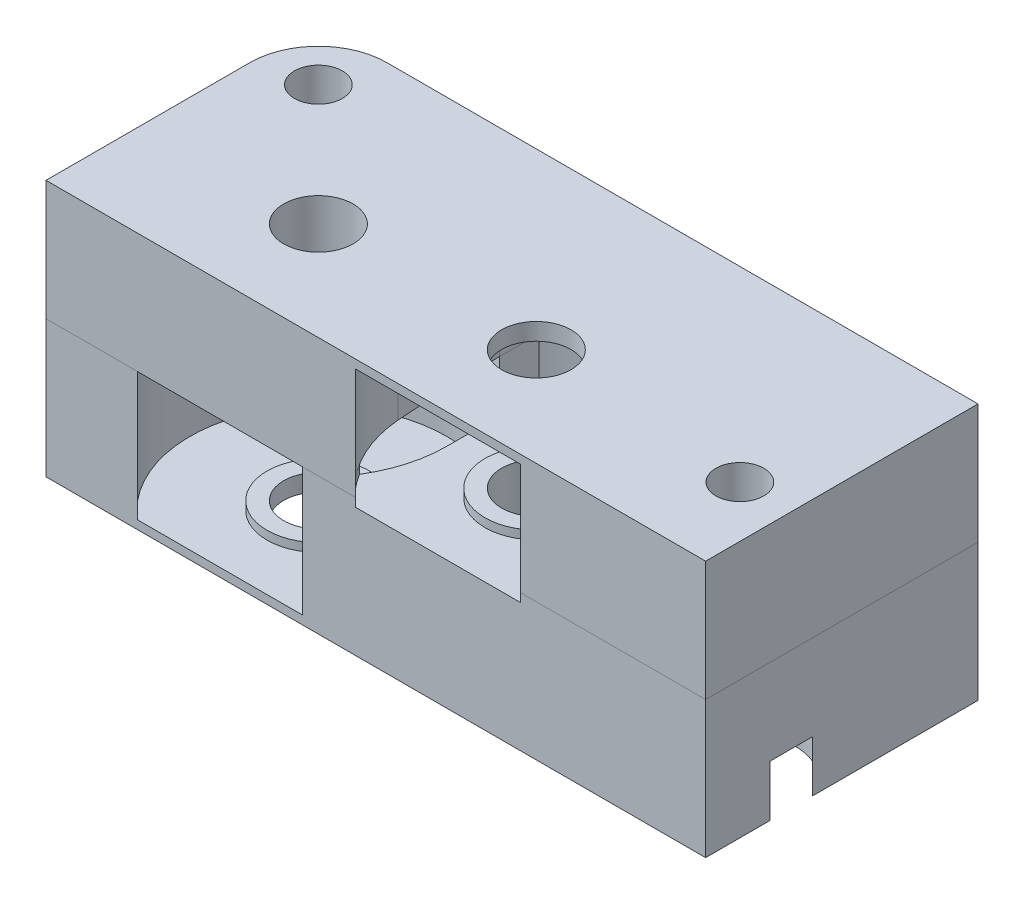
SolidWorks part; units mm, degrees
ref_plane "Front Plane" through (0, 0, 0) normal (0, 0, 1) x (1, 0, 0)
ref_plane "Top Plane" through (0, 0, 0) normal (0, 1, 0) x (1, 0, 0)
ref_plane "Right Plane" through (0, 0, 0) normal (1, 0, 0) x (0, 0, -1)
sketch "Sketch1" plane through (0, 0, 0) normal (0, 1, 0) x (1, 0, 0)
  line L0 (0, 5.75) -> (38.53, 5.75) construction
  line L1 (0, 0) -> (38.53, 0)
  line L2 (0, 0) -> (0, 15.91)
  line L3 (0, 15.91) -> (38.53, 15.91)
  line L4 (38.53, 0) -> (38.53, 15.91)
  circle A0 centre (10.16, 5.75) radius 2.025
  circle A1 centre (22.89, 5.75) radius 2.025
  circle A2 centre (22.89, 5.75) radius 6 construction
  circle A3 centre (10.16, 5.75) radius 6 construction
  dimension "D3" = 4.05
  dimension "D7" = 12
  dimension "D8" = 12
  dimension "D1" = 5.75
  dimension "D2" = 12.73
  dimension "D4" = 38.53
  dimension "D5" = 10.16
  dimension "D6" = 10.16
extrude "Boss-Extrude1" add sketch "Sketch1" along normal blind 8 contours L2 L3 L4 L1
sketch "Sketch2" plane through (0, 8, 0) normal (0, 1, 0) x (1, 0, 0)
  line L0 (17.66, 5.75) -> (17.66, 15.91)
  line L1 (38.53, 15.91) -> (0, 15.91) construction
  line L2 (17.66, 15.91) -> (15.16, 15.91)
  line L3 (0, 0) -> (0, -1.75)
  line L4 (0, 15.91) -> (0, 0) construction
  line L5 (0, -1.75) -> (10.16, -1.75)
  line L6 (15.16, 11.3402) -> (15.16, 15.91)
  line L7 (5.3447, 0) -> (0, 0)
  arc A0 (10.16, -1.75) -> (17.66, 5.75) centre (10.16, 5.75) ccw
  arc A1 (15.16, 11.3402) -> (5.3447, 0) centre (10.16, 5.75) ccw
  point P7 (0, 0)
  dimension "D1" = 7.5
  dimension "D3" = 2.5
extrude "Cut-Extrude1" cut sketch "Sketch2" against normal offset from surface (7 mm away) 1 up to face at (10.16, 0, -3.725)
sketch "Sketch3" plane through (0, 1, 0) normal (0, 1, 0) x (1, 0, 0)
  line L4 (17.66, 5.75) -> (17.66, 15.91)
  line L5 (17.66, 15.91) -> (15.16, 15.91)
  line L7 (5.3447, 0) -> (14.9753, 0)
  line L8 (17.66, 5.75) -> (17.66, 15.91)
  line L9 (17.66, 15.91) -> (15.16, 15.91)
  line L16 (15.16, 15.91) -> (15.16, 11.3402)
  line L17 (15.16, 15.91) -> (15.16, 11.3402)
  line L18 (5.3447, 0) -> (14.9753, 0)
  circle A0 centre (10.16, 5.75) radius 3
  arc A1 (14.9753, 0) -> (17.66, 5.75) centre (10.16, 5.75) ccw
  arc A2 (14.9753, 0) -> (17.66, 5.75) centre (10.16, 5.75) ccw
  arc A5 (15.16, 11.3402) -> (5.3447, 0) centre (10.16, 5.75) ccw
  arc A6 (15.16, 11.3402) -> (5.3447, 0) centre (10.16, 5.75) ccw
  dimension "D2" = 6
  dimension "D1" = 0
extrude "Cut-Extrude2" cut sketch "Sketch3" against normal blind 0.5
sketch "Sketch5" plane through (0, 8, 0) normal (0, 1, 0) x (1, 0, 0)
  line L2 (17.66, 5.75) -> (17.66, 15.91) construction
  line L6 (17.66, 11.1256) -> (17.66, 5.75)
  circle A0 centre (22.89, 5.75) radius 3
  arc A1 (14.9753, 0) -> (17.66, 5.75) centre (10.16, 5.75) ccw construction
  circle A2 centre (22.89, 5.75) radius 2.025 construction
  arc A4 (16.525, 1.783) -> (17.66, 5.75) centre (10.16, 5.75) ccw
  arc A5 (16.525, 1.783) -> (17.66, 11.1256) centre (22.89, 5.75) ccw
  point P5 (17.66, 14.6335)
  point P9 (16.6678, 5.502)
  point P13 (17.66, 14.5938)
  point P16 (17.66, 9.23)
  dimension "D2" = 6
extrude "Cut-Extrude4" cut sketch "Sketch5" against normal blind 0.5
sketch "Sketch8" plane through (0, 8, 0) normal (0, 1, 0) x (1, 0, 0)
  line L1 (0, 0) -> (18.0747, 0)
  line L4 (27.7053, 0) -> (38.53, 0)
  line L5 (38.53, 0) -> (38.53, 15.91)
  line L6 (38.53, 15.91) -> (17.66, 15.91)
  line L7 (17.66, 15.91) -> (17.66, 11.1256)
  line L8 (27.7053, 0) -> (38.53, 0)
  line L9 (38.53, 0) -> (38.53, 15.91)
  line L10 (38.53, 15.91) -> (17.66, 15.91)
  line L14 (0, 15.91) -> (0, 0)
  line L15 (0, 0) -> (5.3447, 0)
  line L16 (15.16, 11.3402) -> (15.16, 15.91)
  line L17 (15.16, 15.91) -> (0, 15.91)
  line L18 (0, 15.91) -> (0, 0)
  line L21 (15.16, 15.91) -> (0, 15.91)
  line L27 (17.66, 15.91) -> (17.66, 11.1256)
  line L29 (15.16, 11.3402) -> (15.16, 15.91)
  arc A0 (18.0747, 0) -> (15.4153, 5.1339) centre (22.89, 5.75) cw
  arc A1 (27.7053, 0) -> (17.66, 11.1256) centre (22.89, 5.75) ccw
  arc A3 (15.16, 11.3402) -> (5.3447, 0) centre (10.16, 5.75) ccw
  arc A10 (15.16, 11.3402) -> (15.4153, 5.1339) centre (90.7098, 11.3402) ccw
  circle A13 centre (10.16, 5.75) radius 2.025 construction
  circle A14 centre (10.16, 5.75) radius 2.025
  arc A17 (27.7053, 0) -> (17.66, 11.1256) centre (22.89, 5.75) ccw
  point P0 (18.0747, 0)
  dimension "D1" = 0
  dimension "D3" = 0
extrude "Boss-Extrude3" add sketch "Sketch8" along normal blind 6 separate body
sketch "Sketch12" plane through (0, 8, 0) normal (0, -1, 0) x (1, 0, 0)
  line L1 (13.9924, -0.5) -> (6.3276, -0.5)
  line L7 (0, 0) -> (0, -15.91)
  line L8 (0, -15.91) -> (15.16, -15.91)
  line L9 (15.16, -15.91) -> (15.16, -11.3402)
  line L10 (18.0747, 0) -> (0, 0)
  line L14 (14.1522, 0) -> (6.1678, 0) construction
  circle A3 centre (10.16, -5.75) radius 2.025 construction
  circle A7 centre (10.16, -5.75) radius 2.025
  arc A9 (16.2402, -2.2815) -> (14.1522, 0) centre (10.16, -5.75) ccw construction
  arc A11 (6.1678, 0) -> (15.1632, -10.6457) centre (10.16, -5.75) ccw construction
  arc A12 (15.4153, -5.1339) -> (15.16, -11.3402) centre (90.7098, -11.3402) ccw
  arc A15 (18.0747, 0) -> (15.4153, -5.1339) centre (22.89, -5.75) ccw
  arc A16 (15.4153, -5.1339) -> (15.1632, -10.6457) centre (90.7098, -11.3402) ccw construction
  arc A17 (16.2402, -2.2815) -> (15.4153, -5.1339) centre (22.89, -5.75) ccw construction
  arc A18 (15.6707, -2.303) -> (14.917, -5.0928) centre (22.89, -5.75) ccw
  arc A19 (14.917, -5.0928) -> (14.6654, -10.4352) centre (90.7098, -11.3402) ccw
  arc A20 (6.3276, -0.5) -> (14.6654, -10.4352) centre (10.16, -5.75) ccw
  arc A21 (15.6707, -2.303) -> (13.9924, -0.5) centre (10.16, -5.75) ccw
  dimension "D1" = 0
  dimension "D2" = 14
  dimension "D3" = 0.5
extrude "Boss-Extrude5" add sketch "Sketch12" along normal blind 1
sketch "Sketch13" plane through (0, 7, 0) normal (0, -1, 0) x (1, 0, 0)
  line L1 (13.9924, -0.5) -> (6.3276, -0.5)
  line L4 (13.9924, -0.5) -> (6.3276, -0.5)
  circle A4 centre (10.16, -5.75) radius 3.025
  circle A5 centre (10.16, -5.75) radius 2.025 construction
  arc A8 (15.6707, -2.303) -> (13.9924, -0.5) centre (10.16, -5.75) ccw
  arc A9 (6.3276, -0.5) -> (14.6654, -10.4352) centre (10.16, -5.75) ccw
  arc A20 (14.917, -5.0928) -> (14.6654, -10.4352) centre (90.7098, -11.3402) ccw
  arc A21 (15.6707, -2.303) -> (14.917, -5.0928) centre (22.89, -5.75) ccw
  arc A22 (15.6707, -2.303) -> (13.9924, -0.5) centre (10.16, -5.75) ccw
  arc A23 (6.3276, -0.5) -> (14.6654, -10.4352) centre (10.16, -5.75) ccw
  arc A24 (14.917, -5.0928) -> (14.6654, -10.4352) centre (90.7098, -11.3402) ccw
  arc A25 (15.6707, -2.303) -> (14.917, -5.0928) centre (22.89, -5.75) ccw
  dimension "D1" = 0
  dimension "D2" = 1
extrude "Cut-Extrude6" cut sketch "Sketch13" against normal blind 0.5
sketch "Sketch14" plane through (0, 14, 0) normal (0, 1, 0) x (1, 0, 0)
  line L1 (0, 15.91) -> (38.53, 15.91)
  line L2 (0, 15.91) -> (0, 0)
  line L3 (0, 0) -> (38.53, 0)
  line L4 (38.53, 15.91) -> (38.53, 0)
  circle A0 centre (22.89, 5.75) radius 2.025 construction
  circle A1 centre (10.16, 5.75) radius 2.025 construction
  circle A2 centre (22.89, 5.75) radius 2.025
  circle A3 centre (10.16, 5.75) radius 2.025
  point P5 (0, 0)
  point P14 (0, 0)
extrude "Boss-Extrude6" add sketch "Sketch14" along normal blind 1
sketch "Sketch15" plane through (0, 14, 0) normal (0, -1, 0) x (1, 0, 0)
  line L4 (15.16, -11.3402) -> (15.16, -15.91)
  line L10 (15.16, -15.91) -> (17.66, -15.91)
  line L15 (15.16, -11.3402) -> (15.16, -15.91)
  line L18 (15.16, -15.91) -> (17.66, -15.91)
  line L26 (17.66, -15.91) -> (17.66, -11.1256)
  line L28 (17.66, -15.91) -> (17.66, -11.1256)
  line L29 (27.7053, 0) -> (18.0747, 0)
  line L30 (27.7053, 0) -> (18.0747, 0)
  circle A0 centre (22.89, -5.75) radius 3 construction
  circle A1 centre (22.89, -5.75) radius 3
  arc A5 (18.0747, 0) -> (15.4153, -5.1339) centre (22.89, -5.75) ccw
  arc A12 (18.0747, 0) -> (15.4153, -5.1339) centre (22.89, -5.75) ccw
  arc A15 (15.4153, -5.1339) -> (15.16, -11.3402) centre (90.7098, -11.3402) ccw
  arc A17 (15.4153, -5.1339) -> (15.16, -11.3402) centre (90.7098, -11.3402) ccw
  arc A18 (17.66, -11.1256) -> (27.7053, 0) centre (22.89, -5.75) ccw
  arc A19 (17.66, -11.1256) -> (27.7053, 0) centre (22.89, -5.75) ccw
  dimension "D1" = 0
extrude "Cut-Extrude7" cut sketch "Sketch15" against normal blind 0.5
fillet "Fillet1" radius 4 1 edges at (0, 11.5, -15.91)
fillet "Fillet2" radius 4 1 edges at (0, 4, -15.91)
sketch "Sketch23" plane through (0, 8, 0) normal (0, -1, 0) x (1, 0, 0)
  line L1 (38.53, 0) -> (38.53, -15.91) construction
  line L2 (10.16, -5.75) -> (3.1161, -12.7939) construction
  line L3 (0, -11.91) -> (0, 0) construction
  line L4 (0, 0) -> (38.53, 0) construction
  circle A0 centre (3.1161, -12.7939) radius 2.75 construction
  arc A1 (0, -11.91) -> (4, -15.91) centre (4, -11.91) ccw construction
  circle A3 centre (3.1161, -12.7939) radius 1.4
  circle A4 centre (35.53, -5) radius 3 construction
  circle A5 centre (35.53, -5) radius 1.4
  circle A6 centre (10.16, -5.75) radius 2.025 construction
  point P6 (5.0607, -10.8493)
  point P19 (4.1061, -11.8039)
  dimension "D1" = 5.5
  dimension "D2" = 2.8
  dimension "D3" = 6
  dimension "D4" = 2.8
  dimension "D5" = 45
  dimension "D6" = 5
extrude "Cut-Extrude13" cut sketch "Sketch23" against normal through all
hole_wizard "CBORE for M3 SHCS1" positions "Sketch24" profile "Sketch25" counterbore size "M3" standard "ANSI Metric"
sketch "Sketch24" plane through (0, 0, 0) normal (0, -1, 0) x (-1, 0, 0)
  circle A0 centre (-3.1161, 12.7939) radius 1.4 construction
  circle A1 centre (-35.53, 5) radius 1.4 construction
  point P0 (-35.53, 5)
  point P2 (-3.1161, 12.7939)
  point P5 (0, 0)
  point P8 (0, 0)
  point P9 (0, 0)
sketch "Sketch25" plane through (35.53, 0, -5) normal (1, 0, 0) x (0, 0, -1)
  line L0 (0, 0) -> (0, 9.0205)
  line L1 (0, 9.0205) -> (1.7, 7.999)
  line L2 (1.7, 7.999) -> (1.7, 3)
  line L3 (1.7, 3) -> (3.25, 3)
  line L4 (3.25, 3) -> (3.25, 0)
  line L5 (3.25, 0) -> (0, 0)
  line L10 (0, 9.0205) -> (-1.7, 7.999) construction
  line L11 (0, -6.35) -> (0, 107.95) construction
  dimension "Hole Dia." = 3.4
  dimension "Hole Depth" = 7.999
  dimension "C'Bore Dia." = 6.5
  dimension "C'Bore Depth" = 3
  dimension "Drill Angle" = 118
